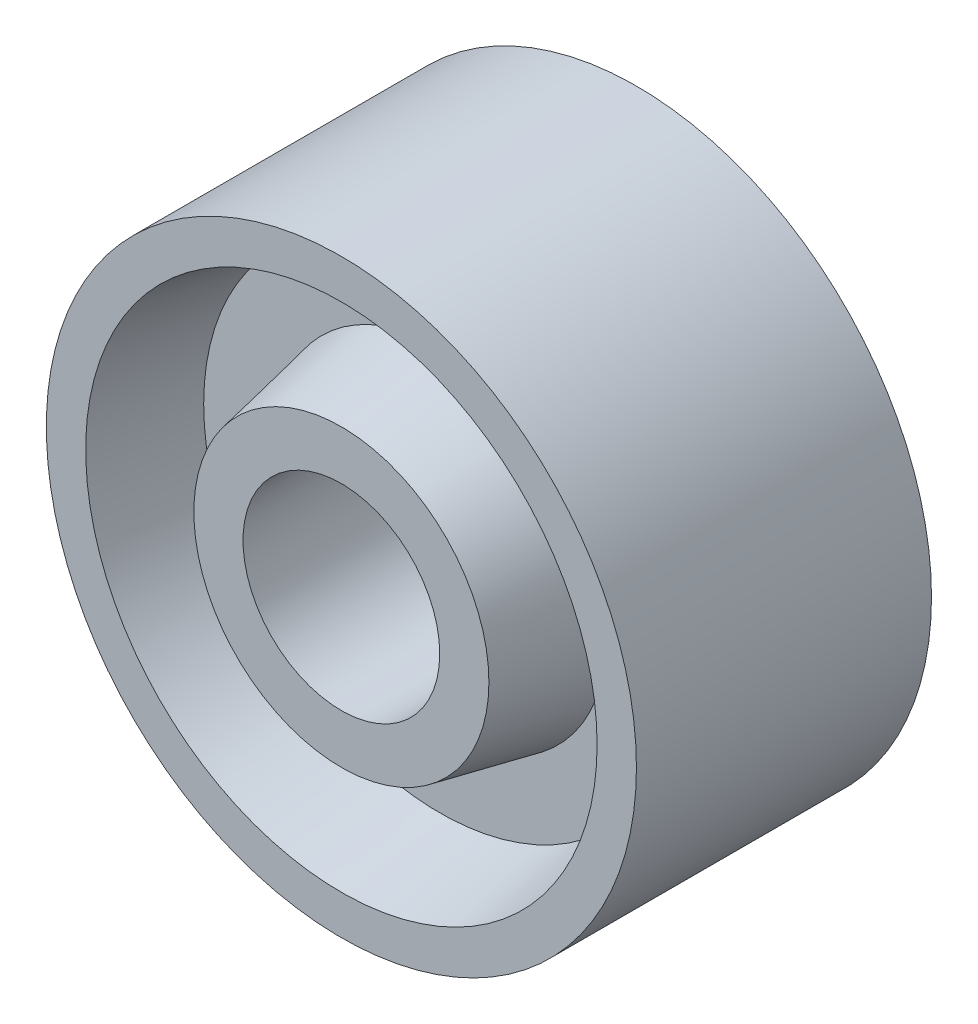
SolidWorks part; units mm, degrees
ref_plane "Ön Düzlem" through (0, 0, 0) normal (0, 0, 1) x (1, 0, 0)
ref_plane "Üst Düzlem" through (0, 0, 0) normal (0, 1, 0) x (1, 0, 0)
ref_plane "Sağ Düzlem" through (0, 0, 0) normal (1, 0, 0) x (0, 0, -1)
sketch "Çizim1" plane through (0, 0, 0) normal (1, 0, 0) x (0, 0, -1)
  line L0 (-34.9296, 0) -> (36.4789, 0) construction
  line L1 (-4.9296, 10) -> (25.0704, 10)
  line L2 (25.0704, 10) -> (25.0704, 15)
  line L3 (25.0704, 15) -> (15.0704, 17)
  line L4 (15.0704, 17) -> (15.0704, 24)
  line L5 (15.0704, 24) -> (25.0704, 26)
  line L6 (25.0704, 26) -> (25.0704, 30)
  line L7 (25.0704, 30) -> (-4.9296, 30)
  line L9 (-4.9296, 26) -> (-4.9296, 30)
  line L10 (5.0704, 24) -> (-4.9296, 26)
  line L11 (5.0704, 17) -> (5.0704, 24)
  line L12 (-4.9296, 15) -> (5.0704, 17)
  line L13 (-4.9296, 10) -> (-4.9296, 15)
  point P5 (0, 0)
  dimension "D1" = 10
  dimension "D2" = 15
  dimension "D3" = 30
  dimension "D4" = 7
  dimension "D5" = 26
  dimension "D7" = 5
  dimension "D10" = 2
revolve "Döndür2" add sketch "Çizim1" angle 360 about L0
